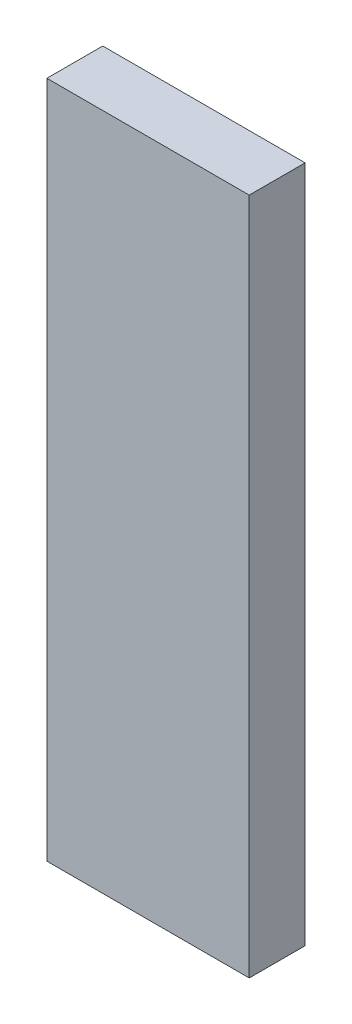
SolidWorks part; units mm, degrees
ref_plane "Front Plane" through (0, 0, 0) normal (0, 0, 1) x (1, 0, 0)
ref_plane "Top Plane" through (0, 0, 0) normal (0, 1, 0) x (1, 0, 0)
ref_plane "Right Plane" through (0, 0, 0) normal (1, 0, 0) x (0, 0, -1)
sketch "Sketch1" plane through (0, 0, 0) normal (0, 0, 1) x (1, 0, 0)
  line L0 (-1.7018, -5.7023) -> (1.7018, -5.7023)
  line L1 (-1.7018, -5.7023) -> (-1.7018, 5.7023)
  line L2 (1.7018, -5.7023) -> (1.7018, 5.7023)
  line L3 (-1.7018, 5.7023) -> (1.7018, 5.7023)
  line L4 (-1.7018, -5.7023) -> (1.7018, 5.7023) construction
  line L5 (1.7018, -5.7023) -> (-1.7018, 5.7023) construction
  point P1 (0, 0)
  dimension "D1" = 3.4036
  dimension "D2" = 11.4046
extrude "Extrude1" add sketch "Sketch1" along normal blind 0.9398
